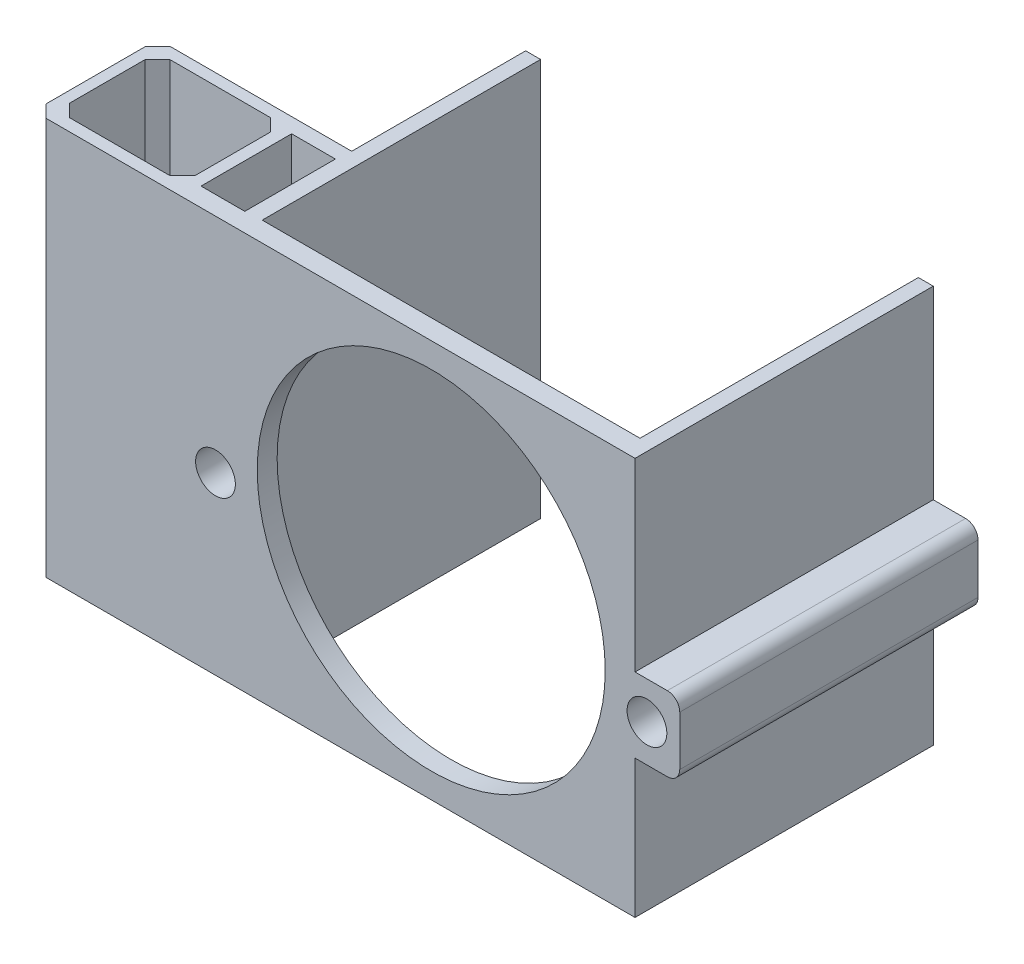
SolidWorks part; units mm, degrees
ref_plane "前视基准面" through (0, 0, 0) normal (0, 0, 1) x (1, 0, 0)
ref_plane "上视基准面" through (0, 0, 0) normal (0, 1, 0) x (1, 0, 0)
ref_plane "右视基准面" through (0, 0, 0) normal (1, 0, 0) x (0, 0, -1)
sketch "草图1" plane through (0, 0, 0) normal (0, 0, 1) x (1, 0, 0)
  line L0 (-20, 32) -> (-20, 0) construction
  line L1 (0, 0) -> (-40, 0)
  line L2 (0, 0) -> (0, 32)
  line L3 (0, 32) -> (-40, 32)
  line L4 (-40, 0) -> (-40, 32)
  circle A0 centre (-20, 16) radius 14
  circle A1 centre (-2.64, 14.11) radius 1.6
  circle A2 centre (-37.36, 14.11) radius 1.6
  dimension "D3" = 28
  dimension "D5" = 3.2
  dimension "D1" = 40
  dimension "D2" = 32
  dimension "D4" = 16
  dimension "D6" = 34.72
  dimension "D7" = 14.11
extrude "凸台-拉伸1" add sketch "草图1" along normal blind 24
sketch "草图3" plane through (0, 0, 0) normal (0, 0, -1) x (-1, 0, 0)
  line L0 (20, 32) -> (20, 0) construction
  line L1 (4.8, 37.5533) -> (35.2, 37.5533)
  line L2 (4.8, 37.5533) -> (4.8, -13.4475)
  line L3 (4.8, -13.4475) -> (35.2, -13.4475)
  line L4 (35.2, 37.5533) -> (35.2, -13.4475)
  line L5 (0, 32) -> (40, 32) construction
  line L6 (40, 0) -> (0, 0) construction
  dimension "D1" = 30.4
extrude "切除-拉伸2" cut sketch "草图3" against normal blind 22.4
sketch "草图4" plane through (0, 0, 0) normal (0, 0, -1) x (-1, 0, 0)
  line L0 (20, 32) -> (20, 0) construction
  line L1 (3.6, 36.2242) -> (-2.5299, 36.2242)
  line L2 (3.6, 36.2242) -> (3.6, 17.11)
  line L3 (3.6, 17.11) -> (-2.5299, 17.11)
  line L4 (-2.5299, 36.2242) -> (-2.5299, 17.11)
  line L5 (35.2, 32) -> (4.8, 32) construction
  line L6 (4.8, 0) -> (35.2, 0) construction
  line L7 (4.8, 32) -> (4.8, 0) construction
  line L8 (42.5299, 36.2242) -> (42.5299, 17.11)
  line L9 (36.4, 17.11) -> (42.5299, 17.11)
  line L10 (36.4, 36.2242) -> (36.4, 17.11)
  line L11 (36.4, 36.2242) -> (42.5299, 36.2242)
  line L12 (2.64, 14.11) -> (37.36, 14.11) construction
  line L15 (36.4, -8.0042) -> (42.5299, -8.0042)
  line L16 (36.4, -8.0042) -> (36.4, 11.11)
  line L17 (36.4, 11.11) -> (42.5299, 11.11)
  line L18 (42.5299, -8.0042) -> (42.5299, 11.11)
  line L19 (-2.5299, -8.0042) -> (-2.5299, 11.11)
  line L20 (3.6, 11.11) -> (-2.5299, 11.11)
  line L21 (3.6, -8.0042) -> (3.6, 11.11)
  line L22 (3.6, -8.0042) -> (-2.5299, -8.0042)
  dimension "D1" = 1.2
  dimension "D2" = 6
extrude "切除-拉伸3" cut sketch "草图4" against normal through all
fillet "圆角1" radius 1 4 edges at (0, 11.11, 12) (0, 17.11, 12) (-40, 11.11, 12) (-40, 17.11, 12)
sketch "草图6" plane through (0, 0, 24) normal (0, 0, 1) x (1, 0, 0)
  line L0 (-20, 32) -> (-20, 0) construction
  line L1 (-36.4, 32) -> (-52, 32)
  line L2 (-36.4, 32) -> (-36.4, 0)
  line L3 (-36.4, 0) -> (-52, 0)
  line L4 (-52, 32) -> (-52, 0)
  line L5 (-3.6, 32) -> (-36.4, 32) construction
  line L6 (-36.4, 0) -> (-3.6, 0) construction
  dimension "D1" = 32
extrude "凸台-拉伸3" add sketch "草图6" against normal blind 10
sketch "草图8" plane through (0, 0, 24) normal (0, 0, 1) x (1, 0, 0)
  circle A0 centre (-37.36, 14.11) radius 1.6
extrude "切除-拉伸4" cut sketch "草图8" against normal through all
sketch "草图9" plane through (0, 32, 0) normal (0, 1, 0) x (1, 0, 0)
  line L0 (-51.1025, -15.9239) -> (-50.1025, -14.9239)
  line L1 (-50.1025, -14.9239) -> (-42.0069, -14.9239)
  line L2 (-51.1025, -15.9239) -> (-51.1025, -22.0122)
  line L3 (-50.1025, -23.0122) -> (-42.0069, -23.0122)
  line L4 (-41.0069, -15.9239) -> (-41.0069, -22.0122)
  line L5 (-42.0069, -14.9239) -> (-41.0069, -15.9239)
  line L6 (-42.0069, -23.0122) -> (-41.0069, -22.0122)
  line L7 (-51.1025, -22.0122) -> (-50.1025, -23.0122)
  point P0 (-51.1025, -14.9239)
  point P1 (-41.0069, -23.0122)
  point P2 (-51.1025, -23.0122)
  point P3 (-41.0069, -14.9239)
  dimension "D1" = 10.0956
  dimension "D2" = 8.0883
extrude "切除-拉伸5" cut sketch "草图9" against normal through all
chamfer "倒角1" distance 1 angle 45 2 edges at (-52, 16, 24) (-52, 16, 14)
sketch "草图10" plane through (0, 32, 0) normal (0, 1, 0) x (1, 0, 0)
  line L1 (-40.0353, -15.1989) -> (-36.5141, -15.1989)
  line L2 (-40.0353, -15.1989) -> (-40.0353, -22.4893)
  line L3 (-40.0353, -22.4893) -> (-36.5141, -22.4893)
  line L4 (-36.5141, -15.1989) -> (-36.5141, -22.4893)
extrude "切除-拉伸6" cut sketch "草图10" against normal blind 15
sketch "草图11" plane through (0, 0, 0) normal (0, -1, 0) x (1, 0, 0)
  line L1 (-40.2833, 22.886) -> (-36.4, 22.886)
  line L2 (-40.2833, 22.886) -> (-40.2833, 15.2485)
  line L3 (-40.2833, 15.2485) -> (-36.4, 15.2485)
  line L4 (-36.4, 22.886) -> (-36.4, 15.2485)
extrude "切除-拉伸7" cut sketch "草图11" against normal blind 11
